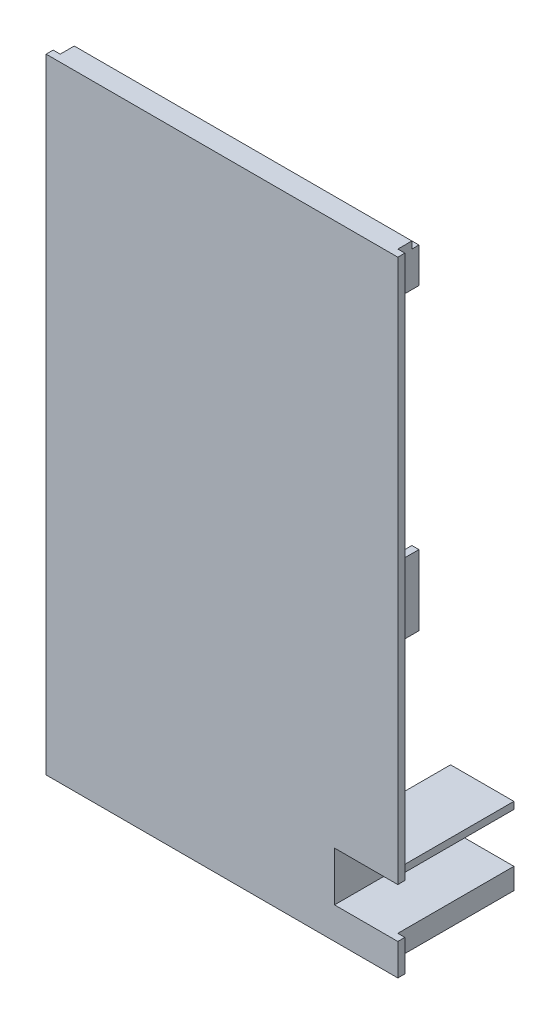
SolidWorks part; units mm, degrees
ref_plane "Front Plane" through (0, 0, 0) normal (0, 0, 1) x (1, 0, 0)
ref_plane "Top Plane" through (0, 0, 0) normal (0, 1, 0) x (1, 0, 0)
ref_plane "Right Plane" through (0, 0, 0) normal (1, 0, 0) x (0, 0, -1)
sketch "Sketch1" plane through (0, 0, 0) normal (0, 0, 1) x (1, 0, 0)
  line L1 (0, 0) -> (100, 0)
  line L2 (0, 0) -> (0, 177.5)
  line L3 (0, 177.5) -> (100, 177.5)
  line L4 (100, 0) -> (100, 177.5)
  dimension "D1" = 177.5
  dimension "D2" = 100
extrude "Boss-Extrude1" add sketch "Sketch1" along normal blind 2
sketch "Sketch2" plane through (0, 0, 0) normal (0, 0, -1) x (-1, 0, 0)
  line L0 (-98, 175.5) -> (-2, 175.5) construction
  line L1 (-2, 175.5) -> (-2, 3) construction
  line L2 (-2, 3) -> (-98, 3) construction
  line L3 (-98, 3) -> (-98, 175.5) construction
  line L4 (-100, 177.5) -> (0, 177.5) construction
  line L5 (0, 177.5) -> (0, 0) construction
  line L6 (-100, 0) -> (-100, 177.5) construction
  line L7 (0, 0) -> (-100, 0) construction
  dimension "D1" = 2
  dimension "D2" = 2
  dimension "D3" = 2
  dimension "D4" = 3
sketch "Sketch3" plane through (0, 0, 0) normal (0, 0, -1) x (-1, 0, 0)
  line L0 (-98, 175.5) -> (-88, 175.5)
  line L1 (-98, 175.5) -> (-2, 175.5) construction
  line L2 (-88, 175.5) -> (-88, 173.5)
  line L3 (-88, 173.5) -> (-96, 173.5)
  line L4 (-96, 173.5) -> (-96, 165.5)
  line L5 (-96, 165.5) -> (-98, 165.5)
  line L6 (-98, 3) -> (-98, 175.5) construction
  line L7 (-98, 165.5) -> (-98, 175.5)
  line L8 (-12, 175.5) -> (-2, 175.5)
  line L9 (-2, 175.5) -> (-2, 165.5)
  line L10 (-2, 175.5) -> (-2, 3) construction
  line L11 (-2, 165.5) -> (-4, 165.5)
  line L12 (-4, 165.5) -> (-4, 173.5)
  line L13 (-4, 173.5) -> (-12, 173.5)
  line L14 (-12, 173.5) -> (-12, 175.5)
  line L15 (-2, 3) -> (-12, 3)
  line L16 (-98, 100.5) -> (-96, 100.5)
  line L17 (-98, 100.5) -> (-98, 80.5)
  line L18 (-98, 80.5) -> (-96, 80.5)
  line L19 (-96, 100.5) -> (-96, 80.5)
  line L20 (-2, 100.5) -> (-4, 100.5)
  line L21 (-2, 100.5) -> (-2, 80.5)
  line L22 (-2, 80.5) -> (-4, 80.5)
  line L23 (-4, 100.5) -> (-4, 80.5)
  line L26 (-2, 3) -> (-98, 3) construction
  line L31 (-12, 3) -> (-12, 5)
  line L32 (-12, 5) -> (-4, 5)
  line L33 (-4, 5) -> (-4, 13)
  line L34 (-4, 13) -> (-2, 13)
  line L35 (-2, 13) -> (-2, 3)
  dimension "D1" = 2
  dimension "D2" = 2
  dimension "D3" = 10
  dimension "D4" = 10
  dimension "D5" = 10
  dimension "D6" = 10
  dimension "D7" = 2
  dimension "D8" = 2
  dimension "D9" = 2
  dimension "D10" = 2
  dimension "D11" = 20
  dimension "D12" = 20
  dimension "D13" = 75
  dimension "D14" = 75
  dimension "D19" = 2
  dimension "D20" = 2
  dimension "D21" = 10
  dimension "D22" = 10
extrude "Boss-Extrude2" add sketch "Sketch3" along normal blind 6
sketch "Sketch4" plane through (0, 0, 0) normal (0, 0, -1) x (-1, 0, 0)
  line L0 (-100, 177.5) -> (0, 177.5) construction
  line L1 (-98, 175.5) -> (-2, 175.5)
  line L2 (-98, 175.5) -> (-98, 177.5)
  line L3 (-98, 177.5) -> (-2, 177.5)
  line L4 (-2, 175.5) -> (-2, 177.5)
extrude "Boss-Extrude3" add sketch "Sketch4" along normal blind 4
sketch "Sketch5" plane through (0, 0, 0) normal (0, 0, -1) x (-1, 0, 0)
  line L0 (-2, 3) -> (-98, 3) construction
  line L20 (-98, 3) -> (-80, 3)
  line L21 (-80, 3) -> (-80, 25)
  line L22 (-80, 25) -> (-98, 25)
  line L23 (-98, 3) -> (-98, 175.5) construction
  line L24 (-98, 25) -> (-98, 23)
  line L25 (-98, 23) -> (-82, 23)
  line L26 (-82, 23) -> (-82, 9)
  line L27 (-82, 9) -> (-98, 9)
  line L28 (-98, 9) -> (-98, 3)
  dimension "D6" = 18
  dimension "D7" = 16
  dimension "D8" = 6
  dimension "D9" = 14
  dimension "D10" = 2
extrude "Boss-Extrude5" add sketch "Sketch5" along normal blind 33
sketch "Sketch7" plane through (0, 0, 0) normal (0, 0, -1) x (-1, 0, 0)
  line L0 (-82, 9) -> (-100, 9)
  line L1 (-100, 0) -> (-100, 177.5) construction
  line L2 (-82, 9) -> (-82, 23)
  line L3 (-82, 23) -> (-100, 23)
  line L4 (-100, 23) -> (-100, 9)
extrude "Cut-Extrude2" cut sketch "Sketch7" against normal through all
